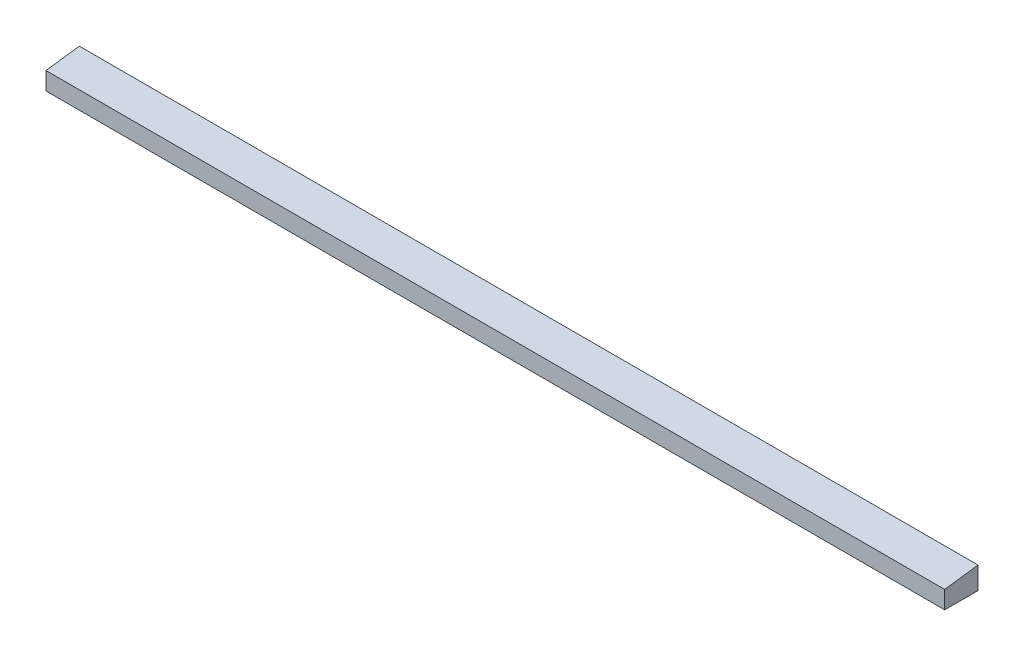
SolidWorks part; units mm, degrees
ref_plane "Front Plane" through (0, 0, 0) normal (0, 0, 1) x (1, 0, 0)
ref_plane "Top Plane" through (0, 0, 0) normal (0, 1, 0) x (1, 0, 0)
ref_plane "Right Plane" through (0, 0, 0) normal (1, 0, 0) x (0, 0, -1)
sketch "Sketch1" plane through (0, 0, 0) normal (0, 0, 1) x (1, 0, 0)
  line L1 (0, 0) -> (514.35, 0)
  line L2 (0, 0) -> (0, 12.7)
  line L3 (0, 12.7) -> (514.35, 12.7)
  line L4 (514.35, 0) -> (514.35, 12.7)
  line L5 (0, 0) -> (514.35, 12.7) construction
  line L6 (0, 12.7) -> (514.35, 0) construction
  point P4 (257.175, 6.35)
  dimension "D1" = 12.7
  dimension "D2" = 514.35
extrude "Boss-Extrude1" add sketch "Sketch1" along normal blind 19.05
sketch "Sketch2" plane through (514.35, 0, 0) normal (1, 0, 0) x (0, 0, -1)
  line L17 (-19.05, 0) -> (-19.05, 12.7) construction
  line L20 (0, 12.7) -> (-19.05, 10.1263)
  line L21 (-19.05, 10.1263) -> (-19.05, 12.7)
  line L22 (-19.05, 12.7) -> (0, 12.7)
  point P0 (-19.05, 10.1263)
extrude "Cut-Extrude1" cut sketch "Sketch2" against normal blind 736.346
